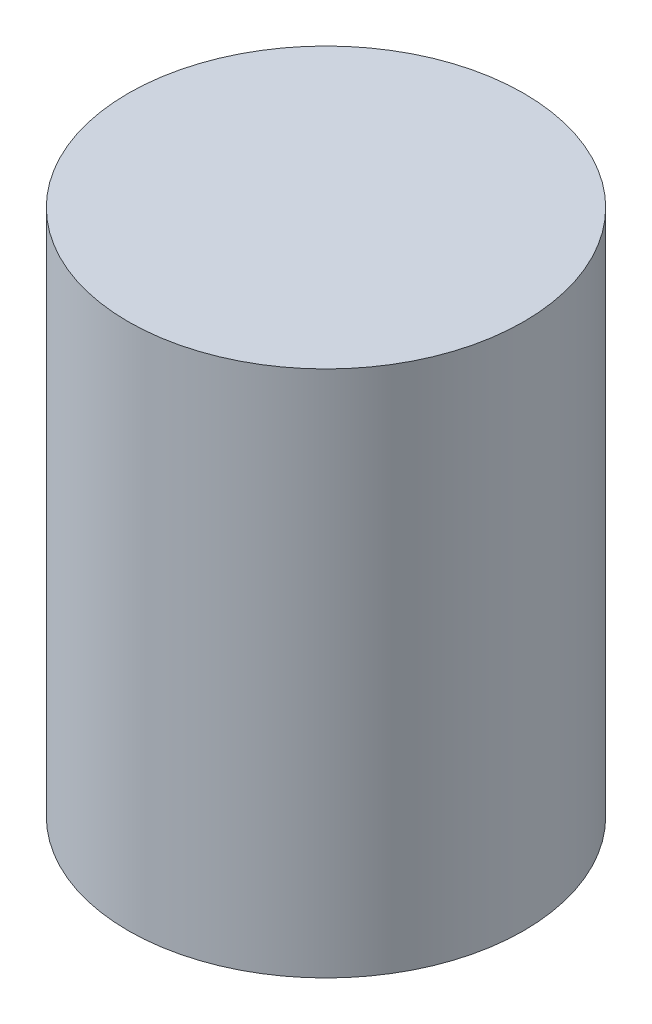
SolidWorks part; units mm, degrees
ref_plane "前视基准面" through (0, 0, 0) normal (0, 0, 1) x (1, 0, 0)
ref_plane "上视基准面" through (0, 0, 0) normal (0, 1, 0) x (1, 0, 0)
ref_plane "右视基准面" through (0, 0, 0) normal (1, 0, 0) x (0, 0, -1)
other "Configuration Table"
sketch "草图1" plane through (0, 0, 0) normal (0, 1, 0) x (1, 0, 0)
  circle A0 centre (0, 0) radius 15
  dimension "D1" = 30
extrude "凸台-拉伸1" add sketch "草图1" along normal blind 40
